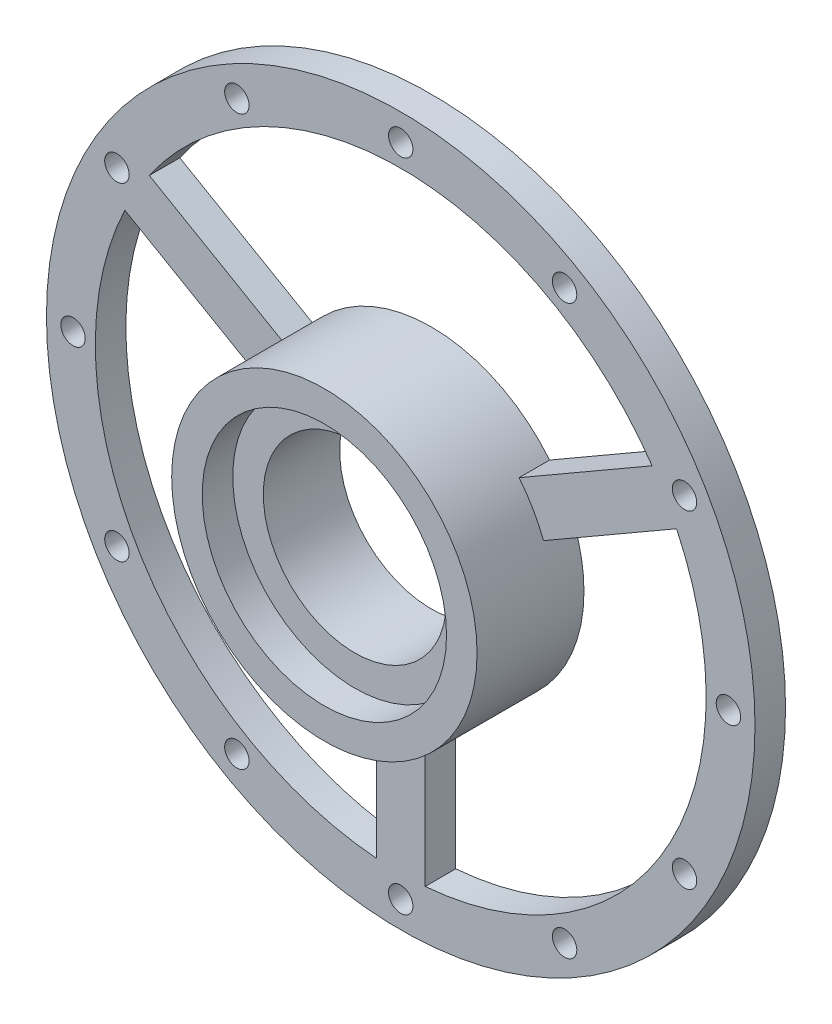
SolidWorks part; units mm, degrees
ref_plane "Front Plane" through (0, 0, 0) normal (0, 0, 1) x (1, 0, 0)
ref_plane "Top Plane" through (0, 0, 0) normal (0, 1, 0) x (1, 0, 0)
ref_plane "Right Plane" through (0, 0, 0) normal (1, 0, 0) x (0, 0, -1)
sketch "Sketch1" plane through (0, 0, 0) normal (1, 0, 0) x (0, 0, -1)
  line L0 (0, 30) -> (-25, 30)
  line L1 (-25, 30) -> (-25, 40)
  line L2 (-25, 40) -> (-35, 40)
  line L3 (-35, 40) -> (-35, 50)
  line L4 (-35, 50) -> (-10, 50)
  line L5 (-10, 50) -> (-10, 116)
  line L6 (-10, 116) -> (0, 116)
  line L7 (0, 116) -> (0, 30)
  line L8 (-100, 0) -> (100, 0) construction
  dimension "D1" = 30
  dimension "D2" = 10
  dimension "D3" = 10
  dimension "D4" = 40
  dimension "D5" = 35
  dimension "D6" = 116
  dimension "D7" = 10
  dimension "D8" = 200
revolve "Revolve1" add sketch "Sketch1" angle 360 about L8
sketch "Sketch2" plane through (0, 0, 10) normal (0, 0, 1) x (1, 0, 0)
  circle A0 centre (0, -107.3) radius 4
  circle A1 centre (-53.65, -92.9245) radius 4
  circle A2 centre (-92.9245, -53.65) radius 4
  circle A3 centre (-107.3, 0) radius 4
  circle A4 centre (-92.9245, 53.65) radius 4
  circle A5 centre (-53.65, 92.9245) radius 4
  circle A6 centre (0, 107.3) radius 4
  circle A7 centre (53.65, 92.9245) radius 4
  circle A8 centre (92.9245, 53.65) radius 4
  circle A9 centre (107.3, 0) radius 4
  circle A10 centre (92.9245, -53.65) radius 4
  circle A11 centre (53.65, -92.9245) radius 4
  point P2 (0, 0)
  point P4 (0, 0)
  point P27 (0, 0)
  point P28 (0, 0)
  point P29 (0, 0)
  point P30 (0, 0)
  point P31 (0, 0)
  point P32 (0, 0)
  point P33 (0, 0)
  point P34 (0, 0)
  point P35 (0, 0)
  point P36 (0, 0)
  point P37 (0, 0)
  point P38 (0, 0)
  point P39 (22.2741, -104.9626)
  point P40 (0, 0)
  dimension "D1" = 107.3
  dimension "D2" = 8
  dimension "D3" = 12
extrude "Cut-Extrude1" cut sketch "Sketch2" against normal up to next
sketch "Sketch3" plane through (0, 0, 10) normal (0, 0, 1) x (1, 0, 0)
  line L0 (-82.325, 56.7679) -> (-38.7434, 31.6061)
  line L1 (-90.325, 42.9115) -> (-46.7434, 17.7497)
  line L2 (-92.9245, 53.65) -> (0, 0) construction
  line L3 (90.325, 42.9115) -> (46.7434, 17.7497)
  line L4 (82.325, 56.7679) -> (38.7434, 31.6061)
  line L5 (-8, -99.6795) -> (-8, -49.3559)
  line L6 (8, -99.6795) -> (8, -49.3559)
  circle A0 centre (0, 0) radius 100
  circle A1 centre (0, 0) radius 50
  circle A3 centre (-92.9245, 53.65) radius 4 construction
  point P8 (0, 0)
  point P9 (0, 0)
  point P22 (0, 0)
  point P23 (0, 0)
  point P24 (46.7434, 17.7497)
  circle M20 centre (0, 0) radius 50
  dimension "D1" = 200
  dimension "D2" = 100
  dimension "D3" = 16
  dimension "D4" = 8
  dimension "D5" = 3
extrude "Cut-Extrude2" cut sketch "Sketch3" against normal up to next contours L4 A0 L0 M20 | L1 A0 L5 M20 | L6 A0 L3 M20
